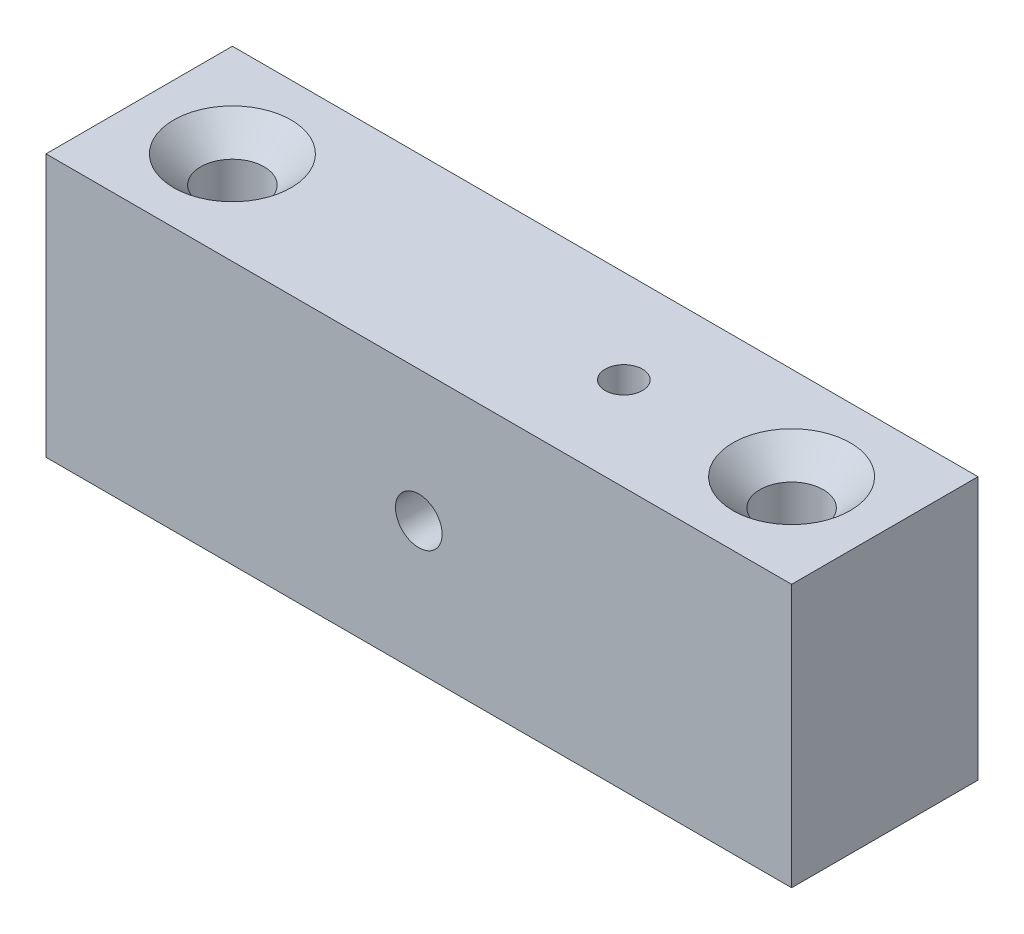
SolidWorks part; units mm, degrees
material "Copper"
ref_plane "Front Plane" through (0, 0, 0) normal (0, 0, 1) x (1, 0, 0)
ref_plane "Top Plane" through (0, 0, 0) normal (0, 1, 0) x (1, 0, 0)
ref_plane "Right Plane" through (0, 0, 0) normal (1, 0, 0) x (0, 0, -1)
sketch "Sketch1" plane through (0, 0, 0) normal (0, 1, 0) x (1, 0, 0)
  line L0 (0, 5) -> (40, 5) construction
  line L1 (0, 0) -> (40, 0)
  line L2 (0, 0) -> (0, 10)
  line L3 (0, 10) -> (40, 10)
  line L4 (40, 0) -> (40, 10)
  line L5 (5, 5) -> (5, 10) construction
  line L6 (35, 10) -> (35, 5) construction
  dimension "D1" = 5
  dimension "D2" = 5
  dimension "D3" = 5
  dimension "D4" = 5
  dimension "D5" = 40
extrude "Boss-Extrude1" add sketch "Sketch1" along normal blind 14.1
sketch "Sketch2" plane through (0, 14.1, 0) normal (0, 1, 0) x (1, 0, 0)
  point P0 (35, 5)
  point P2 (5, 5)
hole_wizard "CSK for M3 Flat Head Machine Screw1" positions "3DSketch1" profile "Sketch3" countersink size "M3" standard "ANSI Metric" end condition through all
sketch3d "3DSketch1"
  point P0 (5, 14.1, -5)
  point P3 (35, 14.1, -5)
sketch "Sketch3" plane through (5, 14.1, -5) normal (1, 0, 0) x (0, 0, 1)
  line L0 (0, 0) -> (0, 14.1)
  line L1 (0, 14.1) -> (1.7, 14.1)
  line L2 (1.7, 14.1) -> (1.7, 1.45)
  line L3 (1.7, 1.45) -> (3.15, 0)
  line L5 (3.15, 0) -> (0, 0)
  line L6 (-1.7, 1.45) -> (-3.15, 0) construction
  line L11 (0, -6.35) -> (0, 107.95) construction
  dimension "Thru Hole Dia." = 3.4
  dimension "Thru Hole Depth" = 14.1
  dimension "Near C'Sink Dia." = 6.3
  dimension "Near C'Sink Angle" = 90
ref_plane "Plane1" through (20, 0, 0) normal (-1, 0, 0) x (0, 0, 1)
sketch "Sketch4" plane through (0, 0, -10) normal (0, 0, -1) x (-1, 0, 0)
  line L0 (-40, 7.05) -> (0, 7.05) construction
  line L1 (-40, 14.1) -> (-40, 0) construction
  line L2 (0, 14.1) -> (0, 0) construction
hole_wizard "M3x0.5 Tapped Hole1" positions "3DSketch2" profile "Sketch5" tap size "M3x0.5" standard "ANSI Metric" end condition through all
sketch3d "3DSketch2"
  line L0 (40, 7.05, -10) -> (0, 7.05, -10) construction
  point P0 (20, 7.05, -10)
  point P4 (20, 7.05, -10)
cosmetic thread "Hole Thread1" parameters "D2"=3
cosmetic thread "Hole Thread2" parameters "D2"=3
sketch "Sketch5" plane through (20, 7.05, -10) normal (1, 0, 0) x (0, 1, 0)
  line L0 (0, 0) -> (0, 10)
  line L1 (0, 10) -> (1.25, 10)
  line L2 (1.25, 10) -> (1.25, 0)
  line L5 (1.25, 0) -> (0, 0)
  line L11 (0, -6.35) -> (0, 107.95) construction
  dimension "Thru Tap Drill Dia." = 2.5
  dimension "Thru Tap Drill Depth" = 10
sketch "Sketch6" plane through (0, 14.1, 0) normal (0, 1, 0) x (1, 0, 0)
  line L0 (40, 5) -> (26, 5) construction
  line L2 (40, 0) -> (40, 10) construction
  dimension "D1" = 14
hole_wizard "Ø2.0mm Dowel Hole1" positions "3DSketch3" profile "Sketch7" hole size "Ø2.0" standard "ANSI Metric" end condition through all
sketch3d "3DSketch3"
  point P0 (26, 14.1, -5)
sketch "Sketch7" plane through (26, 14.1, -5) normal (1, 0, 0) x (0, 0, 1)
  line L0 (0, 0) -> (0, 14.1)
  line L1 (0, 14.1) -> (1, 14.1)
  line L2 (1, 14.1) -> (1, 0)
  line L5 (1, 0) -> (0, 0)
  line L11 (0, -6.35) -> (0, 107.95) construction
  dimension "Thru Hole Dia." = 2
  dimension "Thru Hole Depth" = 14.1
equation "\"D2@Sketch1\"=\"D1@Sketch1\""
equation "\"D3@Sketch1\"=\"D1@Sketch1\""
